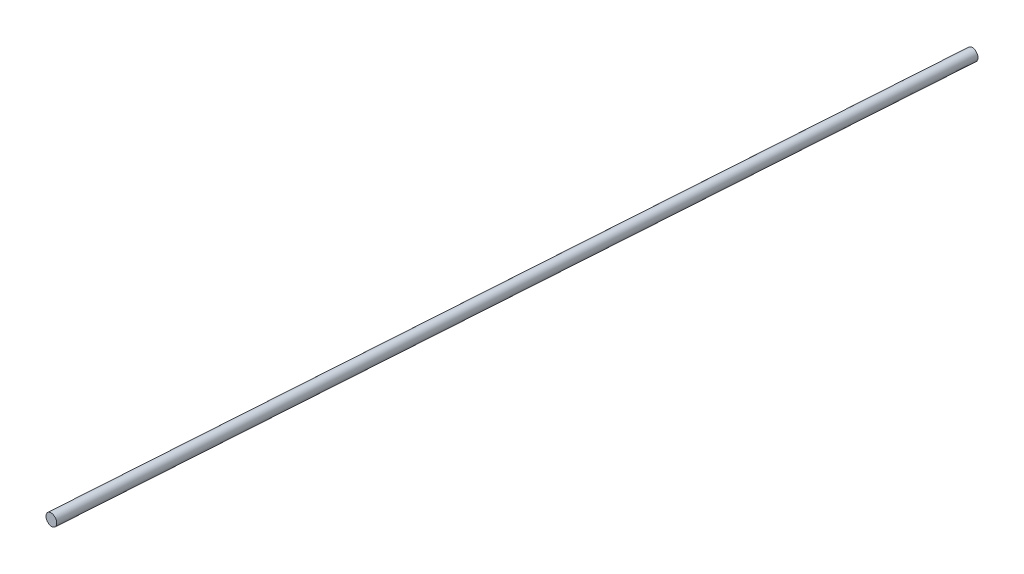
SolidWorks part; units mm, degrees
material "Stainless Steel (ferritic)"
ref_plane "Front Plane" through (0, 0, 0) normal (0, 0, 1) x (1, 0, 0)
ref_plane "Top Plane" through (0, 0, 0) normal (0, 1, 0) x (1, 0, 0)
ref_plane "Right Plane" through (0, 0, 0) normal (1, 0, 0) x (0, 0, -1)
sketch "Sketch1" plane through (0, 0, 0) normal (0, 1, 0) x (1, 0, 0)
  line L0 (-60, 26.2547) -> (60, 26.2547)
  line L1 (60, 26.2547) -> (40, -273.7453)
  line L2 (40, -273.7453) -> (-40, -273.7453)
  line L3 (-40, -273.7453) -> (-60, 26.2547)
  point P2 (0, 26.2547)
  point P5 (0, -273.7453)
  dimension "D1" = 120
  dimension "D2" = 80
  dimension "D3" = 300
ref_plane "Plane1" through (40, 0, 273.7453) normal (-0.0665, 0, 0.9978) x (0.9978, 0, 0.0665)
sketch "Sketch2" plane through (40, 0, 273.7453) normal (-0.0665, 0, 0.9978) x (0.9978, 0, 0.0665)
  circle A0 centre (0.3088, 0) radius 1
  dimension "D1" = 2
extrude "Boss-Extrude1" add sketch "Sketch2" against normal blind 150
